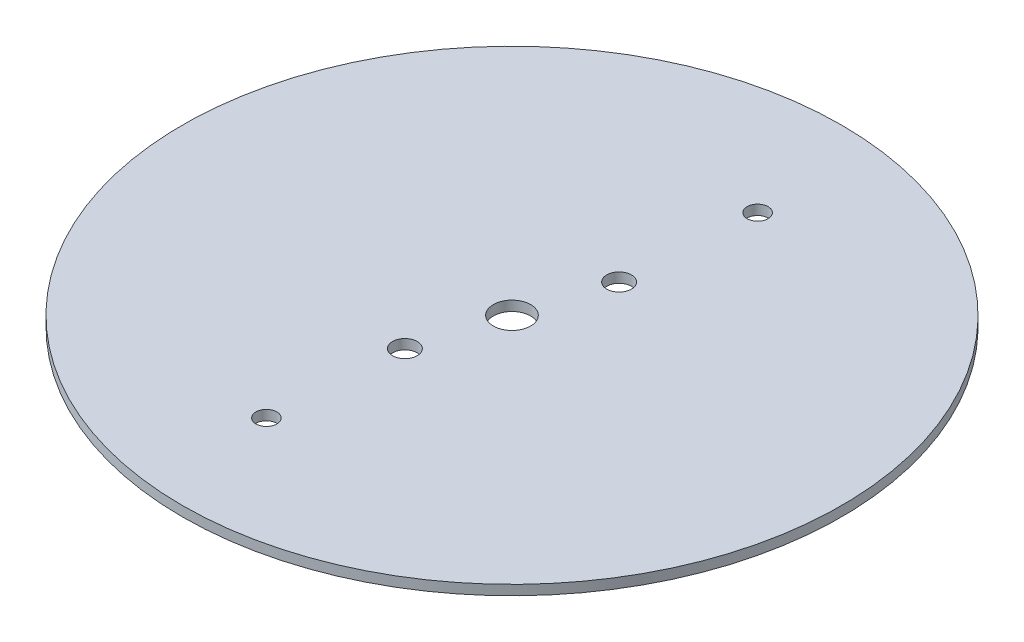
SolidWorks part; units mm, degrees
material "A-Glass Fiber"
ref_plane "Front Plane" through (0, 0, 0) normal (0, 0, 1) x (1, 0, 0)
ref_plane "Top Plane" through (0, 0, 0) normal (0, 1, 0) x (1, 0, 0)
ref_plane "Right Plane" through (0, 0, 0) normal (1, 0, 0) x (0, 0, -1)
sketch "Sketch1" plane through (0, 0, 0) normal (0, 1, 0) x (1, 0, 0)
  line L0 (1.5, 5) -> (0, 0) construction
  line L1 (0, 20) -> (0, -20) construction
  line L2 (0, 0) -> (-1.5, -5) construction
  circle A0 centre (0, 0) radius 20
  circle A1 centre (0, 0) radius 1.1303
  circle A2 centre (1.5, 5) radius 0.75
  circle A3 centre (-1.5, -5) radius 0.75
  circle A4 centre (2.058, 12.8467) radius 0.635
  circle A5 centre (-2.058, -12.8467) radius 0.635
  point P16 (-2.058, -13.4817)
  dimension "D1" = 40
  dimension "D5" = 2.2606
  dimension "D6" = 1.5
  dimension "D7" = 1.5
  dimension "D2" = 1.5
  dimension "D3" = 5
  dimension "D4" = 5
  dimension "D8" = 2.058
  dimension "D9" = 12.8467
  dimension "D10" = 12.8467
  dimension "D11" = 2.058
extrude "PCB" add sketch "Sketch1" along normal blind 0.6 contours A0 | A3 | A1 | A2 | A5 | A4
sketch "Sketch2" plane through (0, 0.6, 0) normal (0, 1, 0) x (1, 0, 0)
  line L0 (0, 0) -> (0, 20) construction
  circle A0 centre (0, 0) radius 20 construction
  point P0 (0, 0)
